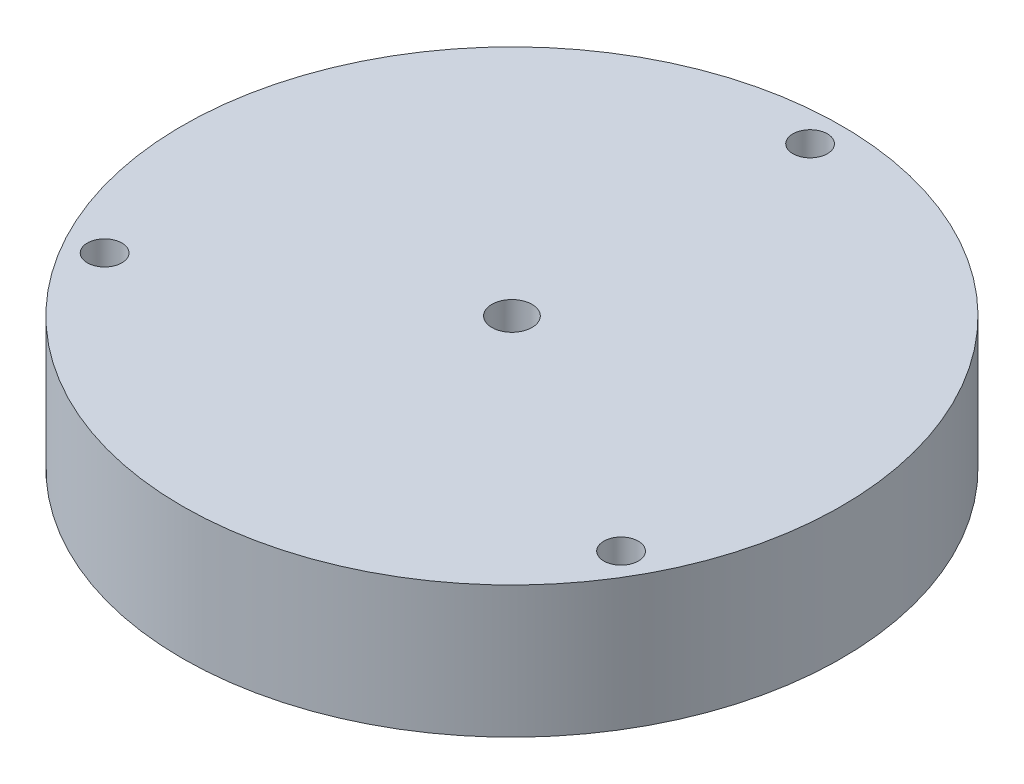
SolidWorks part; units mm, degrees
ref_plane "Plan de face" through (0, 0, 0) normal (0, 0, 1) x (1, 0, 0)
ref_plane "Plan de dessus" through (0, 0, 0) normal (0, 1, 0) x (1, 0, 0)
ref_plane "Plan de droite" through (0, 0, 0) normal (1, 0, 0) x (0, 0, -1)
sketch "Esquisse1" plane through (0, 0, 0) normal (0, 1, 0) x (1, 0, 0)
  line L0 (0, 55.0784) -> (0, -55.7052) construction
  line L1 (-4, 47.5) -> (-4, 50.3413) construction
  line L2 (4, 47.5) -> (4, 50.3413) construction
  line L3 (0, 0) -> (68.6571, 39.6392) construction
  line L4 (0, 0) -> (-63.5298, 36.6789) construction
  line L5 (-4, 48.1274) -> (-4, 47.5)
  line L6 (4, 48.1274) -> (4, 47.5)
  line L7 (43.6796, -20.5996) -> (43.1362, -20.2859)
  line L8 (39.6796, -27.5278) -> (39.1362, -27.2141)
  line L9 (-39.6796, -27.5278) -> (-39.1362, -27.2141)
  line L10 (-43.6796, -20.5996) -> (-43.1362, -20.2859)
  circle A0 centre (0, 0) radius 52.5
  circle A1 centre (0, 0) radius 50.5 construction
  circle A2 centre (0, 47.5) radius 4
  arc A3 (6.2474, 50.1121) -> (43.7343, 25.25) centre (0, 0) cw
  arc A4 (-6.2474, 50.1121) -> (-43.7343, 25.25) centre (0, 0) ccw
  arc A5 (4, 48.1274) -> (6.2474, 50.1121) centre (6, 48.1274) cw
  arc A6 (-4, 48.1274) -> (-6.2474, 50.1121) centre (-6, 48.1274) ccw
  arc A7 (46.522, -19.6456) -> (43.7343, 25.25) centre (0, 0) ccw
  circle A8 centre (41.1362, -23.75) radius 4
  arc A9 (40.2746, -30.4665) -> (0, -50.5) centre (0, 0) cw
  arc A10 (39.6796, -27.5278) -> (40.2746, -30.4665) centre (38.6796, -29.2599) cw
  arc A11 (43.6796, -20.5996) -> (46.522, -19.6456) centre (44.6796, -18.8676) ccw
  arc A12 (-40.2746, -30.4665) -> (0, -50.5) centre (0, 0) ccw
  circle A13 centre (-41.1362, -23.75) radius 4
  arc A14 (-46.522, -19.6456) -> (-43.7343, 25.25) centre (0, 0) cw
  arc A15 (-43.6796, -20.5996) -> (-46.522, -19.6456) centre (-44.6796, -18.8676) cw
  arc A16 (-39.6796, -27.5278) -> (-40.2746, -30.4665) centre (-38.6796, -29.2599) ccw
  point P49 (0, 0)
  dimension "D1" = 105
  dimension "D2" = 2
  dimension "D3" = 2
  dimension "D4" = 8
  dimension "D5" = 47.5
  dimension "D6" = 60
  dimension "D7" = 60
  dimension "D8" = 3
extrude "Boss.-Extru.1" add sketch "Esquisse1" along normal blind 18 contours A0 A16 L9 A13 L10 A15 A14 A4 A6 L5 A2 L6 A5 A3 A7 A11 L7 A8 L8 A10 A9 A12 | A13 | A8 | A2 A9
sketch "Esquisse2" plane through (0, 18, 0) normal (0, 1, 0) x (1, 0, 0)
  circle A1 centre (0, 0) radius 52.5
  circle A2 centre (0, 0) radius 52.5
  dimension "D1" = 0
extrude "Boss.-Extru.2" add sketch "Esquisse2" along normal blind 3
sketch "Esquisse3" plane through (0, 0, 0) normal (0, -1, 0) x (1, 0, 0)
  circle A0 centre (0, -47.5) radius 2.75
  circle A1 centre (0, 0) radius 52.5
  circle A2 centre (0, 0) radius 52.5
  circle A3 centre (-41.1362, 23.75) radius 2.75
  circle A4 centre (41.1362, 23.75) radius 2.75
  point P13 (0, 0)
  dimension "D2" = 5.5
  dimension "D1" = 0
  dimension "D3" = 3
extrude "Enlèv. mat.-Extru.2" cut sketch "Esquisse3" against normal through all from offset 3 contours A4 | A3 | A0 offset against normal yes
sketch "Esquisse4" plane through (0, 0, 0) normal (0, -1, 0) x (1, 0, 0)
  arc A0 (4, -47.5) -> (-4, -47.5) centre (0, -47.5) ccw construction
  arc A1 (4, -47.5) -> (-4, -47.5) centre (0, -47.5) ccw
  circle A2 centre (0, -47.5) radius 1.55
  circle A3 centre (-41.1362, 23.75) radius 1.55
  circle A4 centre (41.1362, 23.75) radius 1.55
  point P11 (0, 0)
  dimension "D1" = 3
  dimension "D2" = 3.1
extrude "Enlèv. mat.-Extru.3" cut sketch "Esquisse4" against normal through all contours A2 | A3 | A4
sketch "Esquisse5" plane through (0, 21, 0) normal (0, 1, 0) x (1, 0, 0)
  line L0 (-57.8947, 998.3227) -> (0, 0)
  line L1 (0, 0) -> (57.8947, 998.3227)
  line L2 (-57.8947, 998.3227) -> (57.8947, 998.3227)
  line L3 (893.5202, -449.023) -> (835.6254, -549.2997)
  line L4 (0, 0) -> (835.6254, -549.2997)
  line L5 (893.5202, -449.023) -> (0, 0)
  line L6 (-835.6254, -549.2997) -> (-893.5202, -449.023)
  line L7 (0, 0) -> (-893.5202, -449.023)
  line L8 (-835.6254, -549.2997) -> (0, 0)
  circle A0 centre (0, 0) radius 1000 construction
  circle A1 centre (0, 47.5) radius 2.75 construction
  circle A2 centre (0, 0) radius 52.5
  circle A3 centre (0, 0) radius 52.5
  circle A4 centre (0, 47.5) radius 2.75 construction
  point P19 (0, 0)
  dimension "D1" = 0
  dimension "D2" = 2000
  dimension "D3" = 115.7895
  dimension "D4" = 3
  dimension "D5" = 6.638
sketch "Esquisse6" plane through (0, 18, 0) normal (0, -1, 0) x (1, 0, 0)
  circle A0 centre (0, 0) radius 6
  dimension "D1" = 12
extrude "Boss.-Extru.3" add sketch "Esquisse6" along normal blind 10
sketch "Esquisse7" plane through (0, 21, 0) normal (0, 1, 0) x (1, 0, 0)
  circle A0 centre (0, 0) radius 3.2
  dimension "D1" = 6.4
extrude "Enlèv. mat.-Extru.5" cut sketch "Esquisse7" against normal through all
